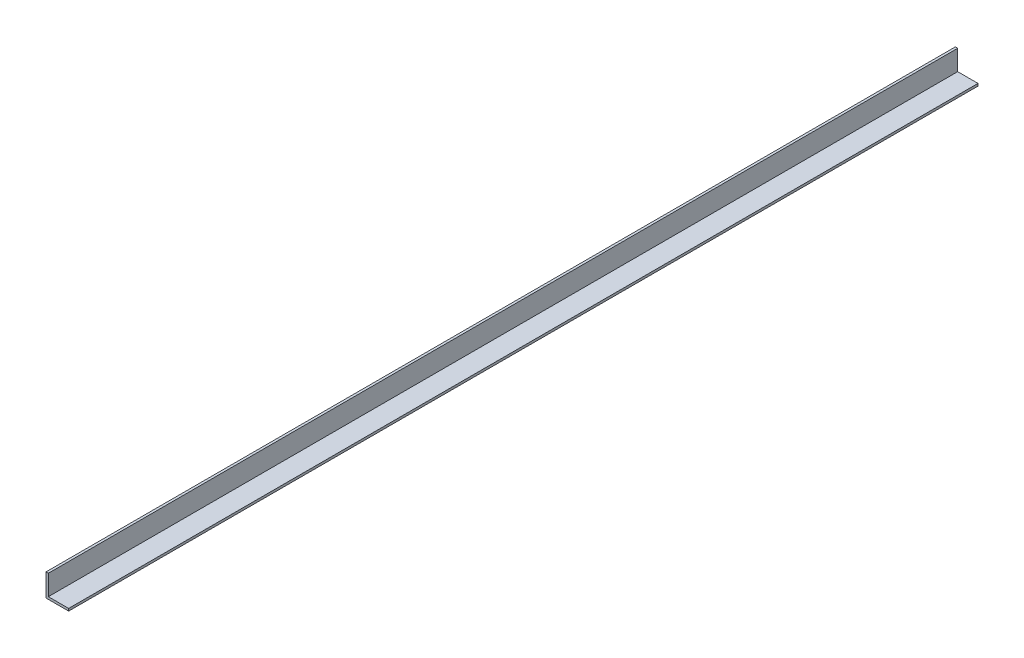
SolidWorks part; units mm, degrees
material "ASTM A36 Acero"
ref_plane "Alzado" through (0, 0, 0) normal (0, 0, 1) x (1, 0, 0)
ref_plane "Planta" through (0, 0, 0) normal (0, 1, 0) x (1, 0, 0)
ref_plane "Vista lateral" through (0, 0, 0) normal (1, 0, 0) x (0, 0, -1)
sketch "Croquis1" plane through (0, 0, 0) normal (0, 0, 1) x (1, 0, 0)
  line L0 (0, 152) -> (0, 0)
  line L1 (0, 0) -> (152, 0)
  line L2 (152, 0) -> (152, 15.88)
  line L3 (152, 15.88) -> (15.88, 15.88)
  line L4 (15.88, 15.88) -> (15.88, 152)
  line L5 (15.88, 152) -> (0, 152)
  dimension "D1" = 15.88
  dimension "D2" = 152
extrude "Saliente-Extruir1" add sketch "Croquis1" against normal blind 6100
